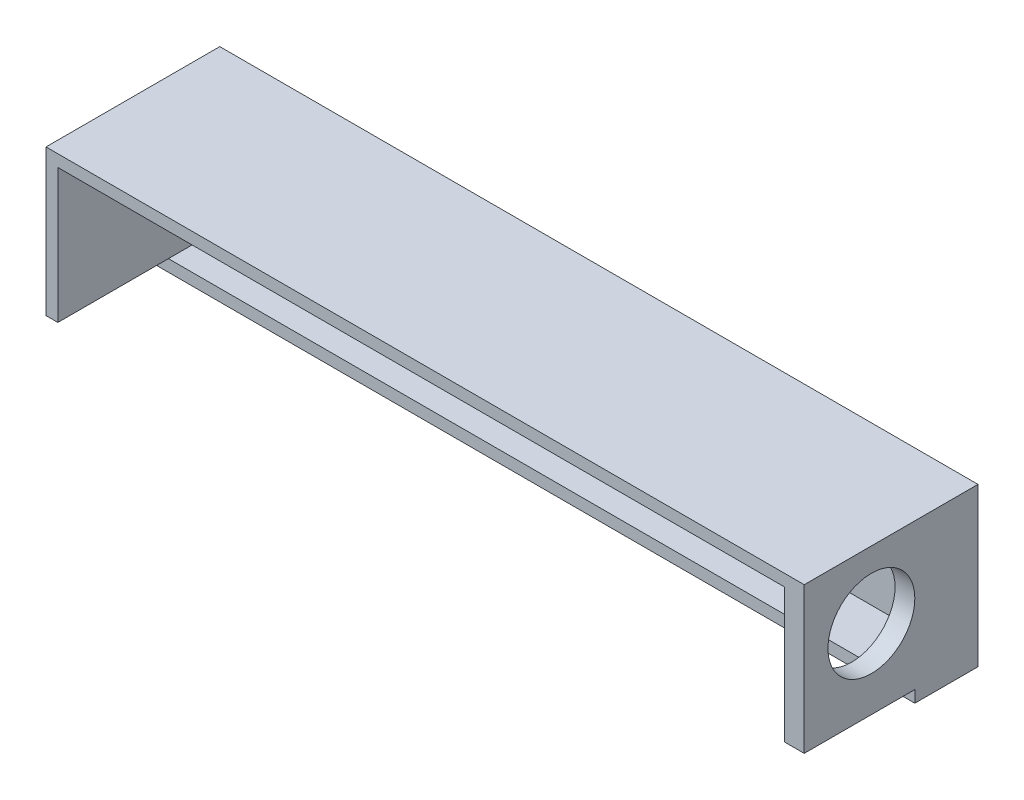
SolidWorks part; units mm, degrees
ref_plane "Спереди" through (0, 0, 0) normal (0, 0, 1) x (1, 0, 0)
ref_plane "Сверху" through (0, 0, 0) normal (0, 1, 0) x (1, 0, 0)
ref_plane "Справа" through (0, 0, 0) normal (1, 0, 0) x (0, 0, -1)
sketch "Эскиз1" plane through (0, 0, 0) normal (0, 0, 1) x (1, 0, 0)
  line L1 (46.5, -10) -> (-46.5, -10)
  line L2 (46.5, -10) -> (46.5, 10)
  line L3 (46.5, 10) -> (-46.5, 10)
  line L4 (-46.5, -10) -> (-46.5, 10)
  line L5 (46.5, -10) -> (-46.5, 10) construction
  line L6 (46.5, 10) -> (-46.5, -10) construction
  point P0 (0, 0)
  dimension "D1" = 20
  dimension "D2" = 93
extrude "Бобышка-Вытянуть1" add sketch "Эскиз1" along normal blind 1.5
sketch "Эскиз2" plane through (0, 0, 1.5) normal (0, 0, 1) x (1, 0, 0)
  line L0 (44, 8.5) -> (-45, 8.5)
  line L1 (46.5, -10) -> (-46.5, -10)
  line L2 (46.5, -10) -> (46.5, 10)
  line L3 (46.5, 10) -> (-46.5, 10)
  line L4 (-46.5, -10) -> (-46.5, 10)
  line L5 (46.5, -10) -> (-46.5, 10) construction
  line L6 (46.5, 10) -> (-46.5, -10) construction
  line L7 (-45, -8.5) -> (-45, 8.5)
  line L8 (44, -8.5) -> (-45, -8.5)
  line L9 (44, 8.5) -> (44, -8.5)
  line L10 (44, 10) -> (44, 9.4624)
  line L11 (45, -8.5) -> (-45, -8.5) construction
  line L12 (45, -8.5) -> (45, 8.5) construction
  line L13 (45, 8.5) -> (-45, 8.5) construction
  point P0 (0, 0)
  point P11 (44, 0)
  dimension "D1" = 1.5
extrude "Бобышка-Вытянуть2" add sketch "Эскиз2" along normal blind 20.5
sketch "Эскиз3" plane through (46.5, 0, 0) normal (1, 0, 0) x (0, 0, -1)
  line L0 (-22, -10) -> (0, -10) construction
  line L1 (0, -10) -> (0, 10) construction
  line L3 (-8, -10) -> (-22, -10)
  line L4 (-22, -8.5) -> (-8, -8.5)
  line L5 (-22, -8.5) -> (-22, -10)
  line L6 (-22, -10) -> (-8, -10)
  line L7 (-8, -8.5) -> (-8, -10)
  point P0 (-8, -10)
  point P8 (-22, -8.5)
  line M4 (-22, 10) -> (-22, -10)
  line M5 (-22, -10) -> (0, -10)
  dimension "D1" = 8
  dimension "D2" = 1.5
extrude "Вырез-Вытянуть1" cut sketch "Эскиз3" against normal blind 101.5 contours L7 L4 M4 M5
sketch "Эскиз4" plane through (46.5, 0, 0) normal (1, 0, 0) x (0, 0, -1)
  line L1 (-22, -8.5) -> (-22, 10) construction
  circle A0 centre (-13.5, 1.5) radius 5.5
  point P2 (-13.5, 7)
  point P3 (-8, 1.5)
  point P4 (-13.5, -4)
  point P5 (-19, 1.5)
  dimension "D1" = 11
  dimension "D2" = 1.5
  dimension "D3" = 3
extrude "Вырез-Вытянуть4" cut sketch "Эскиз4" against normal blind 3
sketch "Эскиз6" plane through (-46.5, 0, 0) normal (-1, 0, 0) x (0, 0, 1)
  line L1 (0, 10) -> (22, 10)
  line L2 (0, 10) -> (0, -8.5)
  line L3 (8, -8.5) -> (22, -8.5)
  line L4 (22, 10) -> (22, -8.5)
  line L5 (8, -10) -> (0, -10)
  line L6 (8, -10) -> (8, -8.5)
  line L8 (0, -10) -> (0, -8.5)
extrude "Бобышка-Вытянуть3" add sketch "Эскиз6" along normal blind 3
sketch "Эскиз7" plane through (0, 0, 22) normal (0, 0, 1) x (1, 0, 0)
  line L1 (-45, -8.5) -> (-48, -8.5)
  line L2 (-45, -8.5) -> (-45, 8.5)
  line L3 (-45, 8.5) -> (-48, 8.5)
  line L4 (-48, -8.5) -> (-48, 8.5)
  dimension "D1" = 3
extrude "Вырез-Вытянуть6" cut sketch "Эскиз7" against normal blind 20.5
